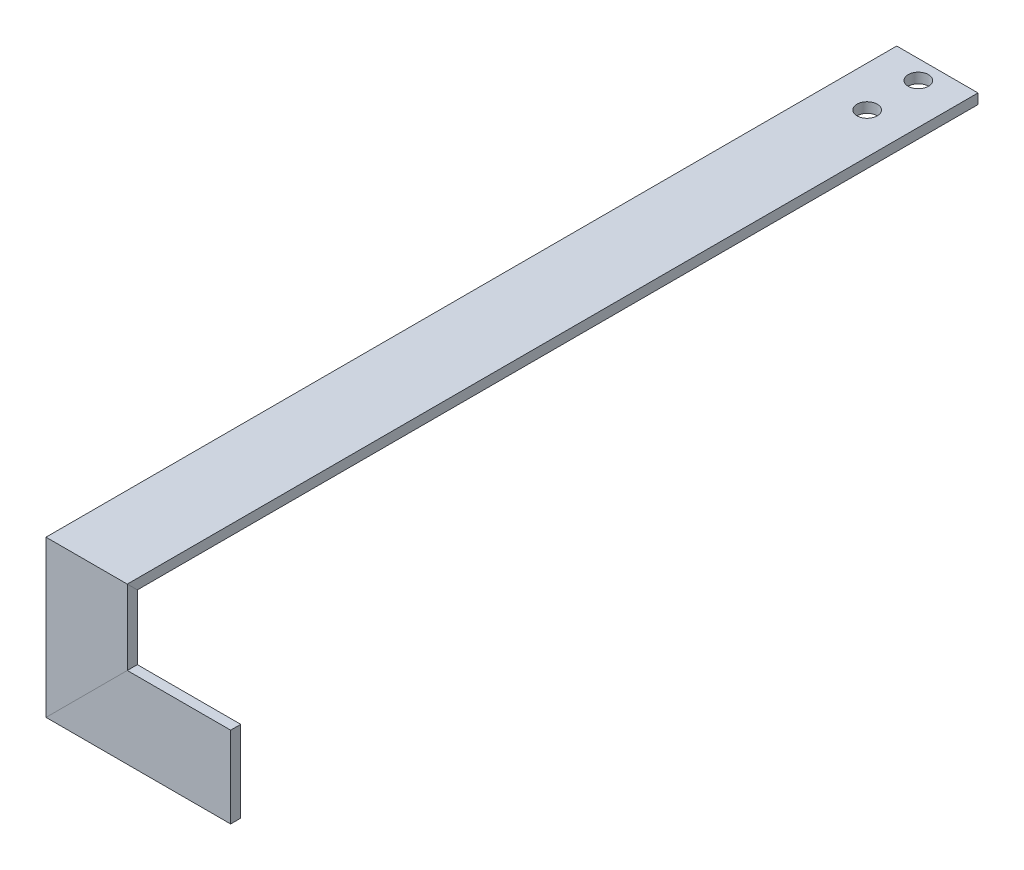
SolidWorks part; units mm, degrees
ref_plane "Alzado" through (0, 0, 0) normal (0, 0, 1) x (1, 0, 0)
ref_plane "Planta" through (0, 0, 0) normal (0, 1, 0) x (1, 0, 0)
ref_plane "Vista lateral" through (0, 0, 0) normal (1, 0, 0) x (0, 0, -1)
sketch "Croquis1" plane through (0, 0, 0) normal (0, 0, 1) x (1, 0, 0)
  line L1 (-25.4, 3.155) -> (25.4, 3.155)
  line L2 (-25.4, 3.155) -> (-25.4, -3.155)
  line L3 (-25.4, -3.155) -> (25.4, -3.155)
  line L4 (25.4, 3.155) -> (25.4, -3.155)
  line L5 (-25.4, 3.155) -> (25.4, -3.155) construction
  line L6 (-25.4, -3.155) -> (25.4, 3.155) construction
  point P0 (0, 0)
  dimension "D1" = 50.8
  dimension "D2" = 6.31
sketch3d "Croquis3D2"
  line L0 (0, 0, 0) -> (0, 0, 528.55)
  line L1 (0, 0, 528.55) -> (0, -69, 528.55)
  line L2 (0, -69, 528.55) -> (90, -69, 528.55)
  dimension "D1" = 528.55
  dimension "D2" = 69
  dimension "D3" = 90
sweep "Barrer1" add profiles "Croquis1" path "Croquis3D2"
sketch "Croquis2" plane through (0, 3.155, 0) normal (0, 1, 0) x (1, 0, 0)
  circle A0 centre (0, -43.8922) radius 6.35
  circle A1 centre (0, -11.8922) radius 6.35
extrude "Cortar-Extruir1" cut sketch "Croquis2" against normal blind 6.31
